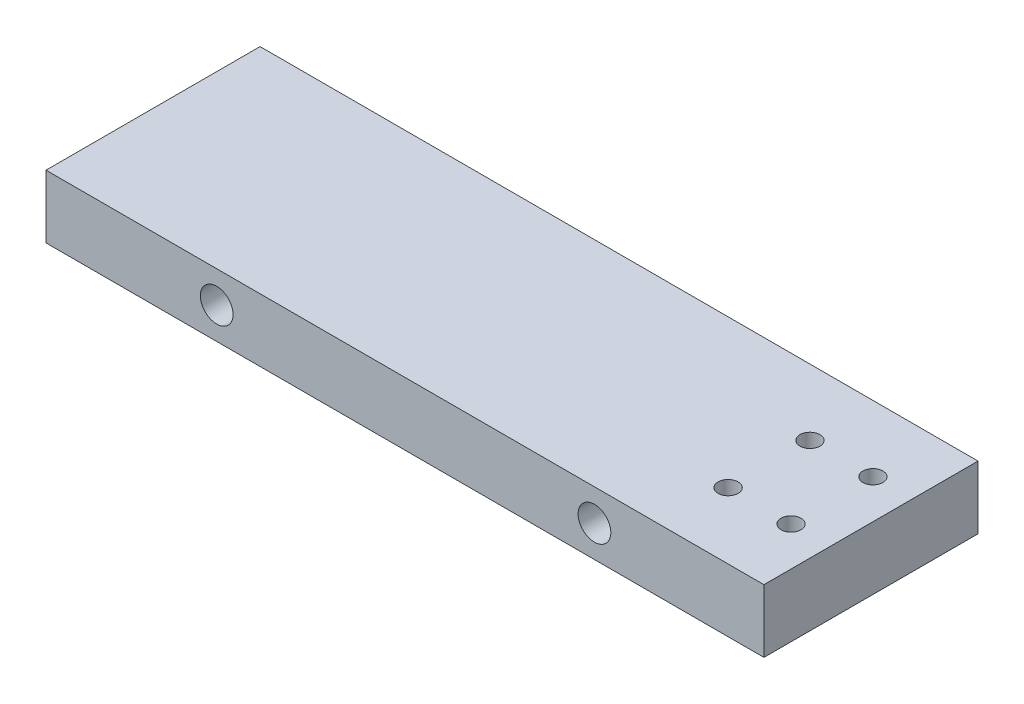
SolidWorks part; units mm, degrees
ref_plane "Front Plane" through (0, 0, 0) normal (0, 0, 1) x (1, 0, 0)
ref_plane "Top Plane" through (0, 0, 0) normal (0, 1, 0) x (1, 0, 0)
ref_plane "Right Plane" through (0, 0, 0) normal (1, 0, 0) x (0, 0, -1)
sketch "Sketch1" plane through (0, 0, 0) normal (0, 1, 0) x (1, 0, 0)
  line L1 (0, 0) -> (114.0288, 0)
  line L2 (0, 0) -> (0, 34)
  line L3 (0, 34) -> (114.0288, 34)
  line L4 (114.0288, 0) -> (114.0288, 34)
  dimension "D1" = 114.0288
  dimension "D2" = 34
extrude "Boss-Extrude1" add sketch "Sketch1" along normal blind 10.01
sketch "Sketch8" plane through (0, 0, -34) normal (0, 0, -1) x (-1, 0, 0)
  line L1 (-114.0288, 10.01) -> (-114.0288, 0) construction
  line L2 (0, 10.01) -> (0, 0) construction
  line L4 (-119.8, 5) -> (-114.0288, 2.5)
  line L9 (0, 7.5) -> (0, 2.5)
  circle A0 centre (-89.8, 5) radius 2.6
  circle A1 centre (-29.8, 5) radius 2.6
  dimension "D2" = 5.2
  dimension "D4" = 5.2
  dimension "D1" = 30
  dimension "D5" = 60
extrude "Cut-Extrude3" cut sketch "Sketch8" against normal through all contours A0 | A1
sketch "Sketch11" plane through (0, 10.01, 0) normal (0, 1, 0) x (1, 0, 0)
  circle A0 centre (110.5288, 10.5) radius 1.59
  circle A1 centre (110.5288, 23.5) radius 1.59
  circle A2 centre (100.5288, 10.5) radius 1.59
  circle A3 centre (100.5288, 23.5) radius 1.59
  dimension "D4" = 3.18
  dimension "D9" = 3.18
  dimension "D2" = 3.18
  dimension "D5" = 3.18
extrude "Cut-Extrude6" cut sketch "Sketch11" against normal through all contours A0 | A1 | A2 | A3
sketch "Sketch12" plane through (114.0288, 0, 0) normal (1, 0, 0) x (0, 0, -1)
  line L1 (0, 10.01) -> (34, 10.01)
  line L2 (0, 10.01) -> (0, 0)
  line L3 (0, 0) -> (34, 0)
  line L4 (34, 10.01) -> (34, 0)
extrude "Boss-Extrude2" add sketch "Sketch12" along normal blind 2.69
sketch "Sketch14" plane through (0, 0, 0) normal (-1, 0, 0) x (0, 0, 1)
  line L1 (-34, 10.01) -> (0, 10.01)
  line L2 (-34, 10.01) -> (-34, 0)
  line L3 (-34, 0) -> (0, 0)
  line L4 (0, 10.01) -> (0, 0)
extrude "Cut-Extrude7" cut sketch "Sketch14" against normal blind 2.69
